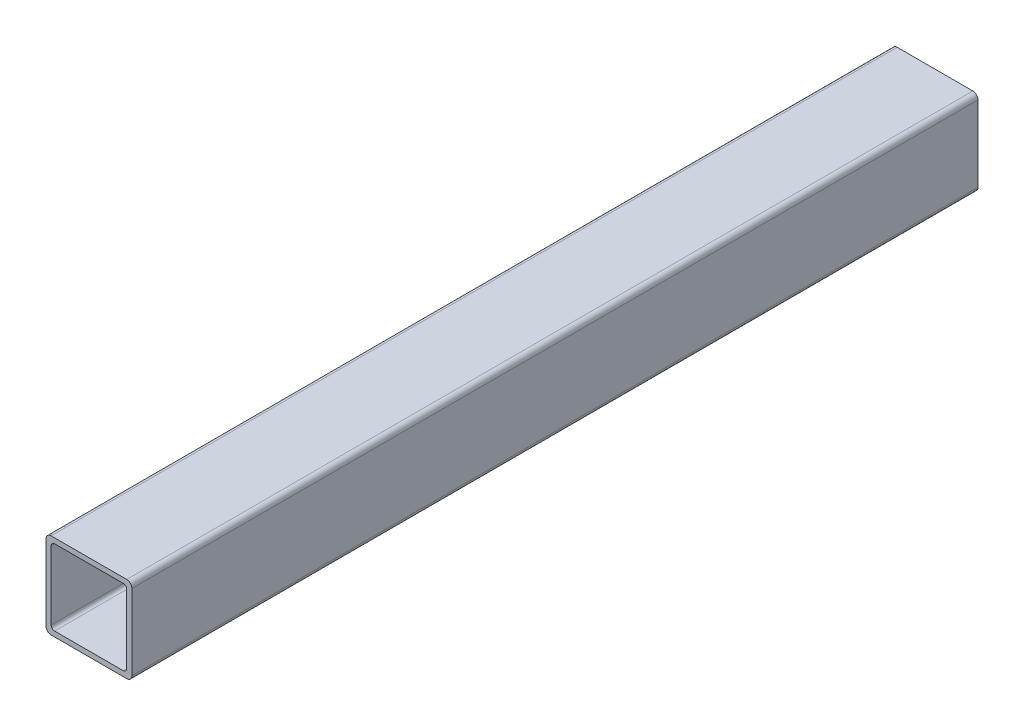
SolidWorks part; units mm, degrees
material "AISI 1020"
ref_plane "Спереди" through (0, 0, 0) normal (0, 0, 1) x (1, 0, 0)
ref_plane "Сверху" through (0, 0, 0) normal (0, 1, 0) x (1, 0, 0)
ref_plane "Справа" through (0, 0, 0) normal (1, 0, 0) x (0, 0, -1)
sketch "Эскиз1" plane through (0, 0, 0) normal (0, 0, 1) x (1, 0, 0)
  line L1 (0, 0) -> (0, 2145) construction
  point P0 (0, 0)
  line B0 (-22, 50) -> (22, 50)
  line B1 (-25, 47) -> (-25, 3)
  line B2 (-22, 0) -> (22, 0)
  line B3 (25, 47) -> (25, 3)
  line B4 (-20, 47) -> (20, 47)
  line B5 (-22, 45) -> (-22, 5)
  line B6 (-20, 3) -> (20, 3)
  line B7 (22, 45) -> (22, 5)
  arc B8 (-25, 3) -> (-22, 0) centre (-22, 3) ccw
  arc B9 (22, 0) -> (25, 3) centre (22, 3) ccw
  arc B10 (22, 50) -> (25, 47) centre (22, 47) cw
  arc B11 (-22, 50) -> (-25, 47) centre (-22, 47) ccw
  arc B12 (-22, 5) -> (-20, 3) centre (-20, 5) ccw
  arc B13 (20, 3) -> (22, 5) centre (20, 5) ccw
  arc B14 (20, 47) -> (22, 45) centre (20, 45) cw
  arc B15 (-20, 47) -> (-22, 45) centre (-20, 45) ccw
sketch_block_instance "Труба профильная 50х50х3-1"
sketch_block "Труба профильная 50х50х3" parameters "D3"=3, "D4"=2, "D1"=50, "D2"=3
extrude "Бобышка-Вытянуть1" add sketch "Эскиз1" against normal up to vertex (442.5 mm away)
